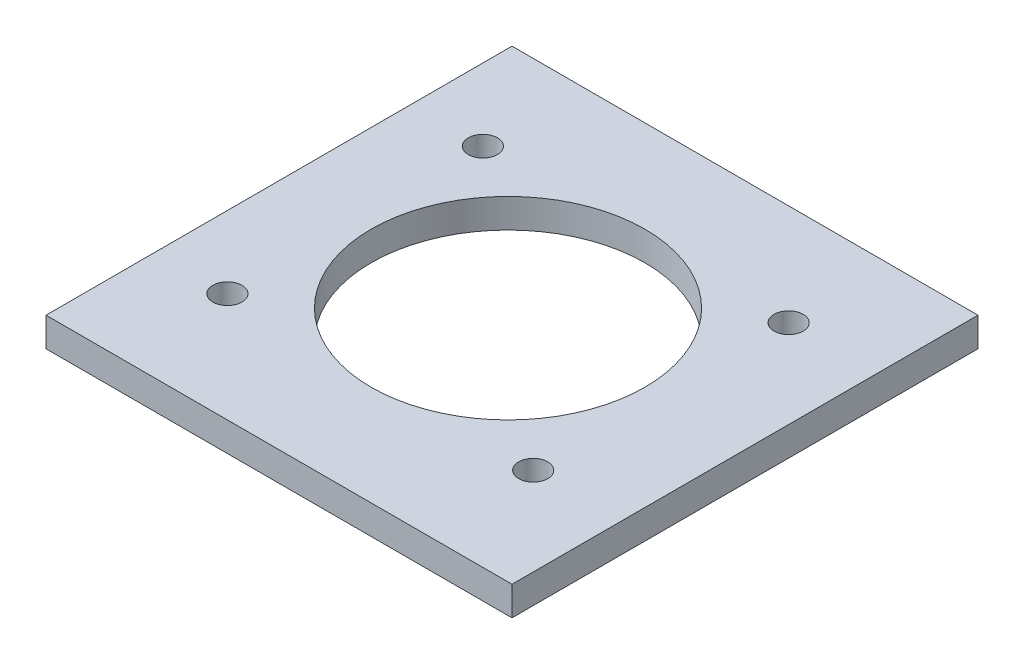
SolidWorks part; units mm, degrees
ref_plane "Front Plane" through (0, 0, 0) normal (0, 0, 1) x (1, 0, 0)
ref_plane "Top Plane" through (0, 0, 0) normal (0, 1, 0) x (1, 0, 0)
ref_plane "Right Plane" through (0, 0, 0) normal (1, 0, 0) x (0, 0, -1)
sketch "Sketch1" plane through (0, 0, 0) normal (0, 1, 0) x (1, 0, 0)
  line L1 (0, 0) -> (64, 0)
  line L2 (0, 0) -> (0, 64)
  line L3 (0, 64) -> (64, 64)
  line L4 (64, 0) -> (64, 64)
  circle A0 centre (30.8929, 32.5589) radius 18.8
  circle A5 centre (9.8979, 15.0139) radius 2
  circle A6 centre (51.8979, 15.0139) radius 2
  circle A7 centre (9.8979, 50.0989) radius 2
  circle A8 centre (51.8929, 50.0989) radius 2
  point P5 (30.8929, 32.5589)
  point P13 (9.8979, 15.0139)
  point P16 (51.8979, 15.0139)
  point P20 (9.8979, 50.0989)
  point P21 (51.8929, 50.0989)
  dimension "D3" = 37.6
  dimension "D4" = 42
  dimension "D6" = 35.085
  dimension "D7" = 21
  dimension "D1" = 64
  dimension "D2" = 64
  dimension "D5" = 41.995
  dimension "D8" = 17.545
extrude "Boss-Extrude4" add sketch "Sketch1" along normal blind 4 contours A8 | A0 | A7 | A5 | A6 | L2 L1 L4 L3
